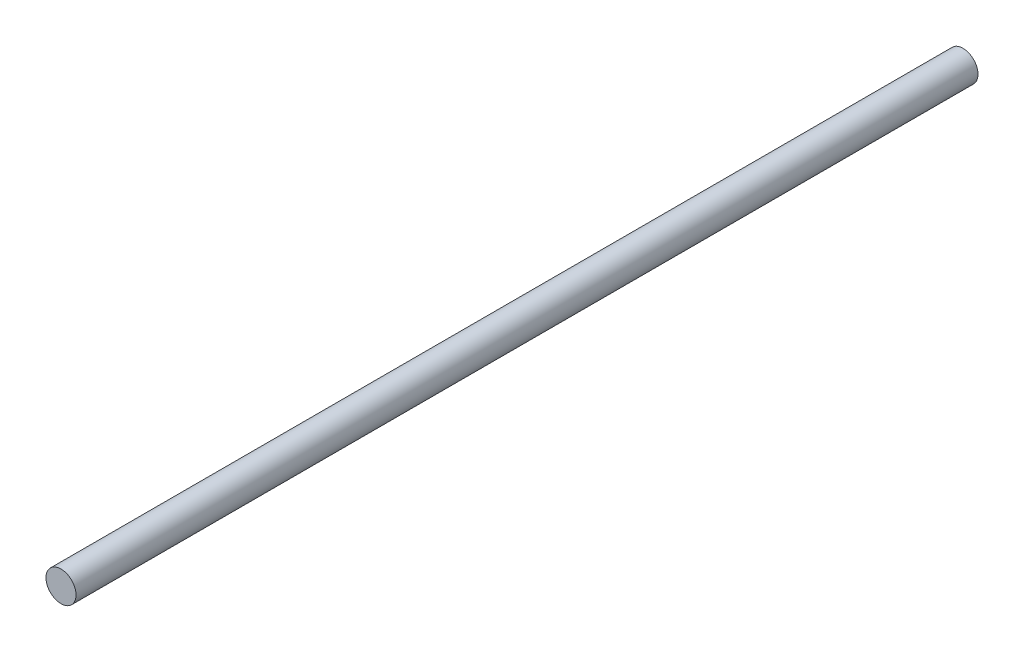
SolidWorks part; units mm, degrees
ref_plane "Front Plane" through (0, 0, 0) normal (0, 0, 1) x (1, 0, 0)
ref_plane "Top Plane" through (0, 0, 0) normal (0, 1, 0) x (1, 0, 0)
ref_plane "Right Plane" through (0, 0, 0) normal (1, 0, 0) x (0, 0, -1)
sketch "Sketch1" plane through (0, 0, 0) normal (0, 0, 1) x (1, 0, 0)
  circle A0 centre (0, 0) radius 12.5
  dimension "D1" = 25
extrude "Boss-Extrude1" add sketch "Sketch1" along normal blind 750
